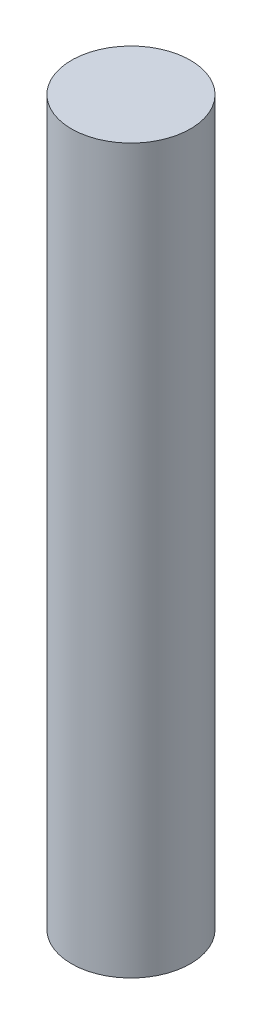
SolidWorks part; units mm, degrees
ref_plane "Front Plane" through (0, 0, 0) normal (0, 0, 1) x (1, 0, 0)
ref_plane "Top Plane" through (0, 0, 0) normal (0, 1, 0) x (1, 0, 0)
ref_plane "Right Plane" through (0, 0, 0) normal (1, 0, 0) x (0, 0, -1)
sketch "Sketch1" plane through (0, 0, 0) normal (0, 1, 0) x (1, 0, 0)
  circle A0 centre (0, 0) radius 2.925
  dimension "D1" = 5.85
extrude "Boss-Extrude1" add sketch "Sketch1" along normal blind 35.56
